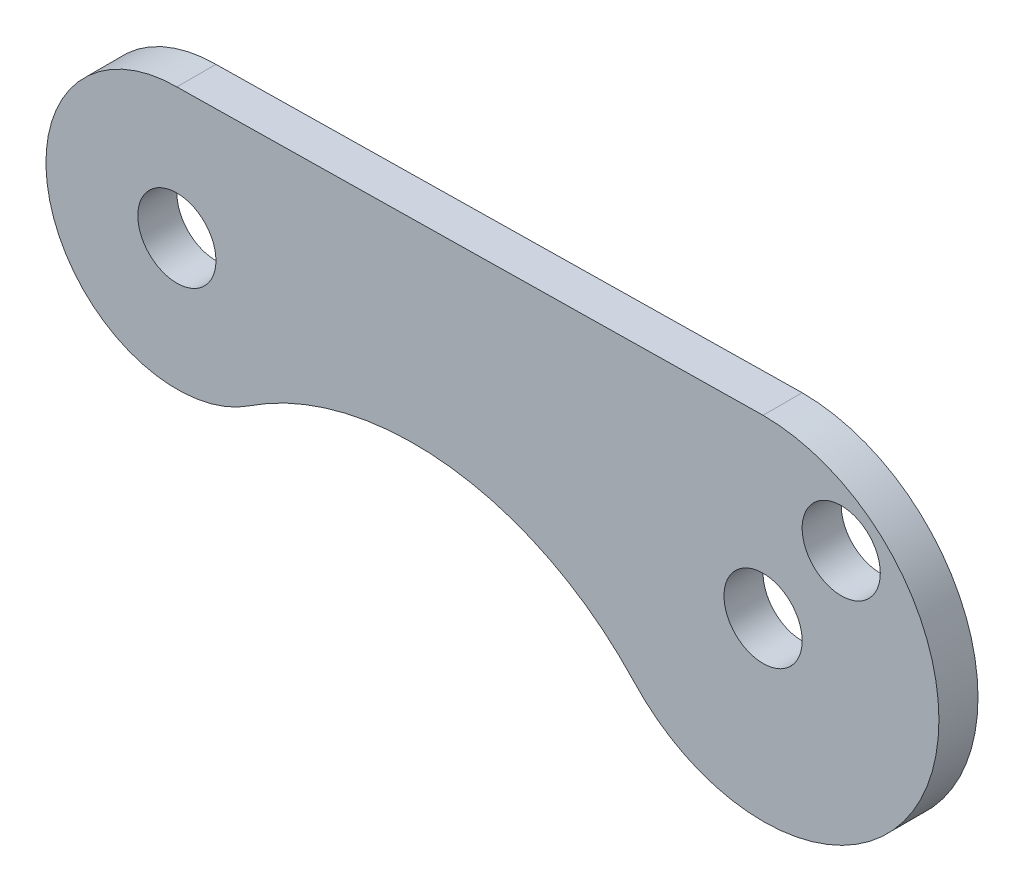
SolidWorks part; units mm, degrees
ref_plane "Front Plane" through (0, 0, 0) normal (0, 0, 1) x (1, 0, 0)
ref_plane "Top Plane" through (0, 0, 0) normal (0, 1, 0) x (1, 0, 0)
ref_plane "Right Plane" through (0, 0, 0) normal (1, 0, 0) x (0, 0, -1)
sketch "Sketch1" plane through (0, 0, 0) normal (0, 0, 1) x (1, 0, 0)
  line L0 (-31.0207, 8.8289) -> (-1.0207, 9.2757)
  arc A0 (-31.0207, 8.8289) -> (-27.3206, -3.4568) centre (-31.0207, 2.1289) ccw
  arc A1 (-7.632, -5.8309) -> (-1.2887, 9.2717) centre (-1.0207, 0.2757) ccw
  arc A2 (-7.632, -5.8309) -> (-27.3206, -3.4568) centre (-18.8713, -16.2121) ccw
  circle A3 centre (-31.0207, 2.1289) radius 2
  circle A4 centre (-1.0207, 0.2757) radius 2
  circle A5 centre (2.9793, 5.2757) radius 2
  point P12 (0, 0)
  dimension "D1" = 30
  dimension "D2" = 18
  dimension "D3" = 13.4
  dimension "D5" = 4
  dimension "D6" = 4
  dimension "D7" = 4
  dimension "D4" = 4
  dimension "D8" = 5
extrude "Boss-Extrude1" add sketch "Sketch1" along normal blind 2 contours A2 A1 L0 A0 A5 A4 A3
